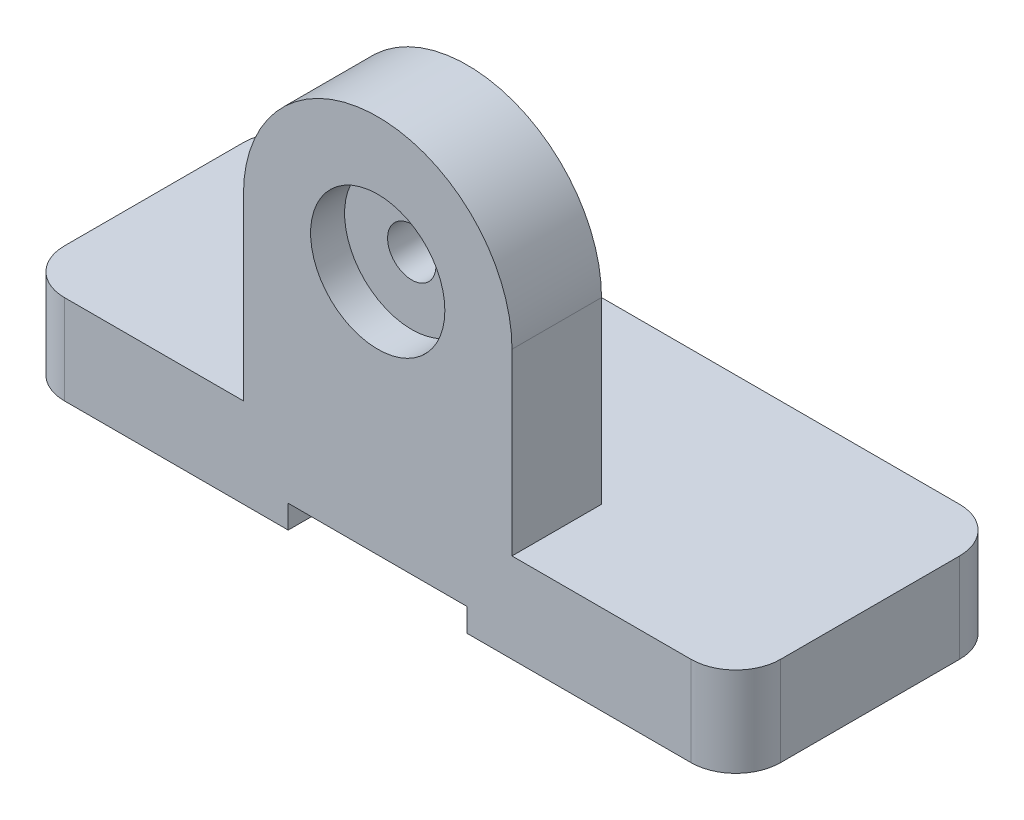
SolidWorks part; units mm, degrees
ref_plane "Front Plane" through (0, 0, 0) normal (0, 0, 1) x (1, 0, 0)
ref_plane "Top Plane" through (0, 0, 0) normal (0, 1, 0) x (1, 0, 0)
ref_plane "Right Plane" through (0, 0, 0) normal (1, 0, 0) x (0, 0, -1)
sketch "Sketch2" plane through (0, 0, 0) normal (0, 1, 0) x (1, 0, 0)
  line L1 (50.8, -19.05) -> (-50.8, -19.05)
  line L2 (50.8, -19.05) -> (50.8, 19.05)
  line L3 (50.8, 19.05) -> (-50.8, 19.05)
  line L4 (-50.8, -19.05) -> (-50.8, 19.05)
  line L5 (50.8, -19.05) -> (-50.8, 19.05) construction
  line L6 (50.8, 19.05) -> (-50.8, -19.05) construction
  point P0 (0, 0)
  dimension "D1" = 101.6
  dimension "D2" = 38.1
extrude "Boss-Extrude1" add sketch "Sketch2" along normal blind 12.7
sketch "Sketch3" plane through (0, 0, 19.05) normal (0, 0, 1) x (1, 0, 0)
  line L0 (-50.8, 0) -> (50.8, 0) construction
  line L1 (-12.7, 0) -> (12.7, 0)
  line L2 (-12.7, 0) -> (-12.7, 3.302)
  line L3 (-12.7, 3.302) -> (12.7, 3.302)
  line L4 (12.7, 0) -> (12.7, 3.302)
  dimension "D1" = 3.302
  dimension "D2" = 25.4
extrude "Cut-Extrude1" cut sketch "Sketch3" against normal through all
sketch "Sketch5" plane through (0, 0, 19.05) normal (0, 0, 1) x (1, 0, 0)
  line L0 (-50.8, 12.7) -> (50.8, 12.7) construction
  line L1 (-19.05, 12.7) -> (19.05, 12.7)
  line L2 (-19.05, 12.7) -> (-19.05, 38.1)
  line L3 (-19.05, 38.1) -> (19.05, 38.1) construction
  line L4 (19.05, 12.7) -> (19.05, 38.1)
  line L5 (0, 0) -> (0, 12.7) construction
  arc A0 (-19.05, 38.1) -> (19.05, 38.1) centre (0, 38.1) cw
  dimension "D1" = 38.1
  dimension "D2" = 25.4
extrude "Boss-Extrude2" add sketch "Sketch5" against normal blind 12.7
hole_wizard "CBORE for #0 Pan Head Machine Screw1" positions "Sketch7" profile "Sketch8" counterbore size "#0" standard "ANSI Inch" end condition through all
sketch "Sketch7" plane through (0, 0, 19.05) normal (0, 0, 1) x (1, 0, 0)
  line L0 (0, 38.1) -> (0, 12.7) construction
  line L1 (0, 12.7) -> (-19.05, 12.7) construction
  point P0 (0, 38.1)
  dimension "D1" = 25.4
sketch "Sketch8" plane through (0, 38.1, 19.05) normal (1, 0, 0) x (0, -1, 0)
  line L0 (0, 0) -> (0, 38.1)
  line L1 (0, 38.1) -> (3.429, 38.1)
  line L3 (3.429, 38.1) -> (3.429, 4.826)
  line L4 (3.429, 4.826) -> (9.525, 4.826)
  line L5 (9.525, 4.826) -> (9.525, 0)
  line L7 (9.525, 0) -> (0, 0)
  line L11 (0, -6.35) -> (0, 107.95) construction
  dimension "Thru Hole Dia." = 6.858
  dimension "Thru Hole Depth" = 38.1
  dimension "C'Bore Dia." = 19.05
  dimension "C'Bore Depth" = 4.826
fillet "Fillet1" radius 6.35 4 edges at (-50.8, 6.35, -19.05) (50.8, 6.35, -19.05) (-50.8, 6.35, 19.05) (50.8, 6.35, 19.05)
